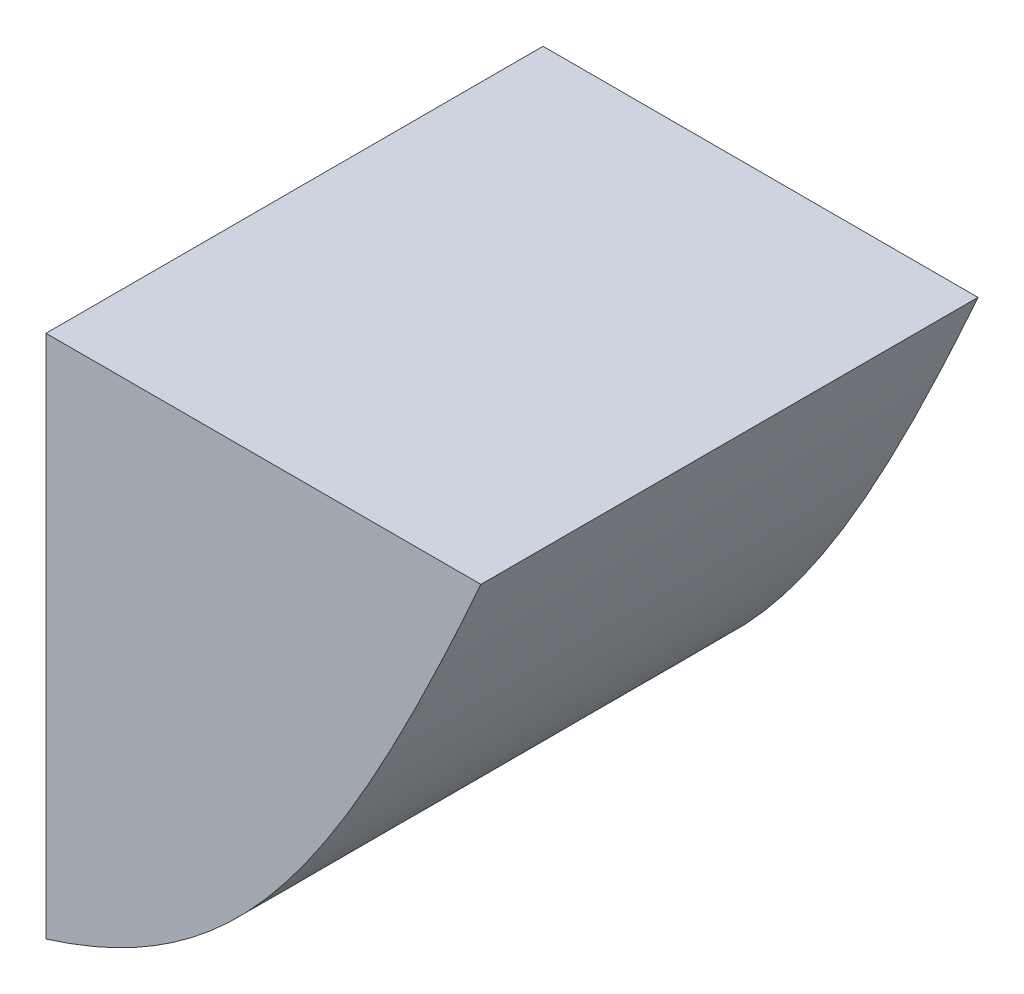
SolidWorks part; units mm, degrees
ref_plane "Front Plane" through (0, 0, 0) normal (0, 0, 1) x (1, 0, 0)
ref_plane "Top Plane" through (0, 0, 0) normal (0, 1, 0) x (1, 0, 0)
ref_plane "Right Plane" through (0, 0, 0) normal (1, 0, 0) x (0, 0, -1)
ref_plane "plane:profile" through (0, 0, 0) normal (0, 0, 1) x (1, 0, 0)
sketch "profile:rational" plane through (0, 0, 0) normal (0, 0, 1) x (1, 0, 0)
  line L0 (12, 9) -> (0, 9)
  line L1 (0, 9) -> (0, 0)
  spline S0 degree 3 poles (0, 0) (4, 0) (8, 0) (12, 9) knots 0 0 0 0 1 1 1 1 weights 1 0.75 1.25 1
extrude "feature:prism" add sketch "profile:rational" along normal blind 8 separate body
sketch "profile:cut" plane through (0, 0, 0) normal (0, 0, 1) x (1, 0, 0)
  line L0 (-2, -2) -> (5, -2)
  line L1 (5, -2) -> (5, 11)
  line L2 (5, 11) -> (-2, 11)
  line L3 (-2, 11) -> (-2, -2)
extrude "feature:trim" cut sketch "profile:cut" along normal through all
